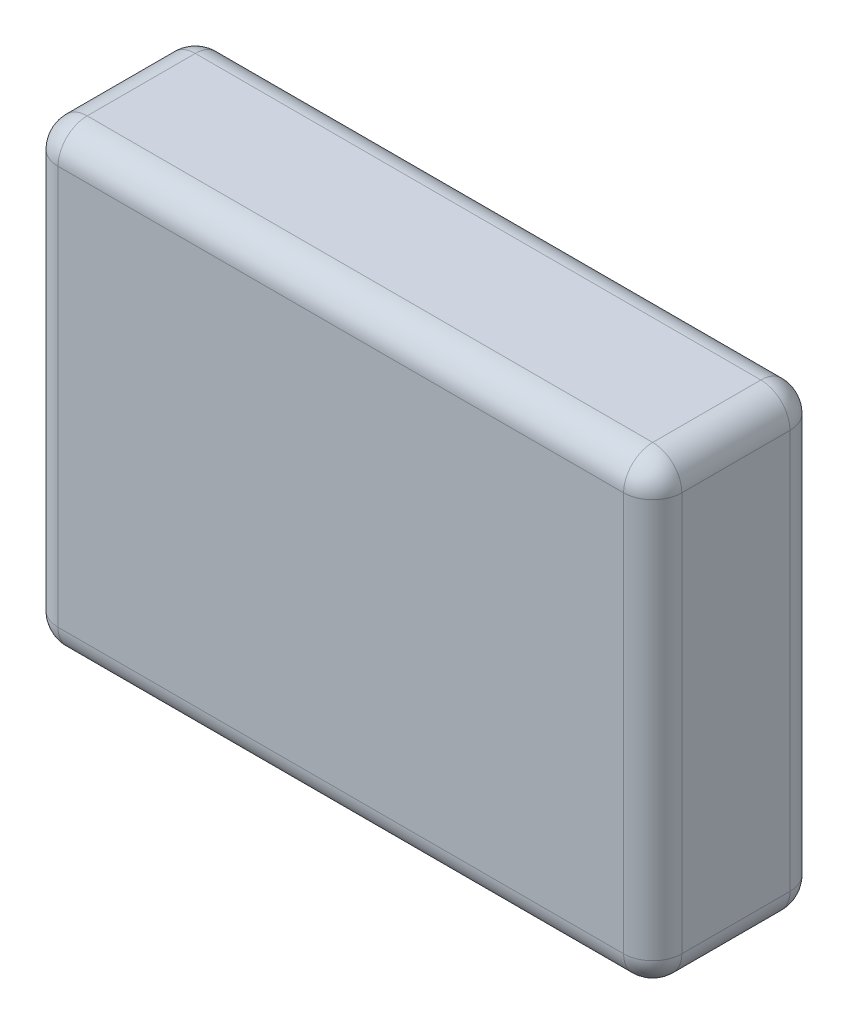
SolidWorks part; units mm, degrees
ref_plane "Front Plane" through (0, 0, 0) normal (0, 0, 1) x (1, 0, 0)
ref_plane "Top Plane" through (0, 0, 0) normal (0, 1, 0) x (1, 0, 0)
ref_plane "Right Plane" through (0, 0, 0) normal (1, 0, 0) x (0, 0, -1)
sketch "Sketch1" plane through (0, 0, 0) normal (0, 0, 1) x (1, 0, 0)
  line L1 (0, 0) -> (750, 0)
  line L2 (0, 0) -> (0, 550)
  line L3 (0, 550) -> (750, 550)
  line L4 (750, 0) -> (750, 550)
  dimension "D1" = 750
  dimension "D2" = 550
extrude "Boss-Extrude1" add sketch "Sketch1" along normal blind 200
fillet "Fillet1" radius 35 12 edges at (0, 0, 100) (750, 0, 100) (750, 550, 100) (0, 550, 100) (375, 550, 200) (750, 275, 200) (375, 0, 200) (0, 275, 200) (375, 0, 0) (750, 275, 0) (375, 550, 0) (0, 275, 0)
